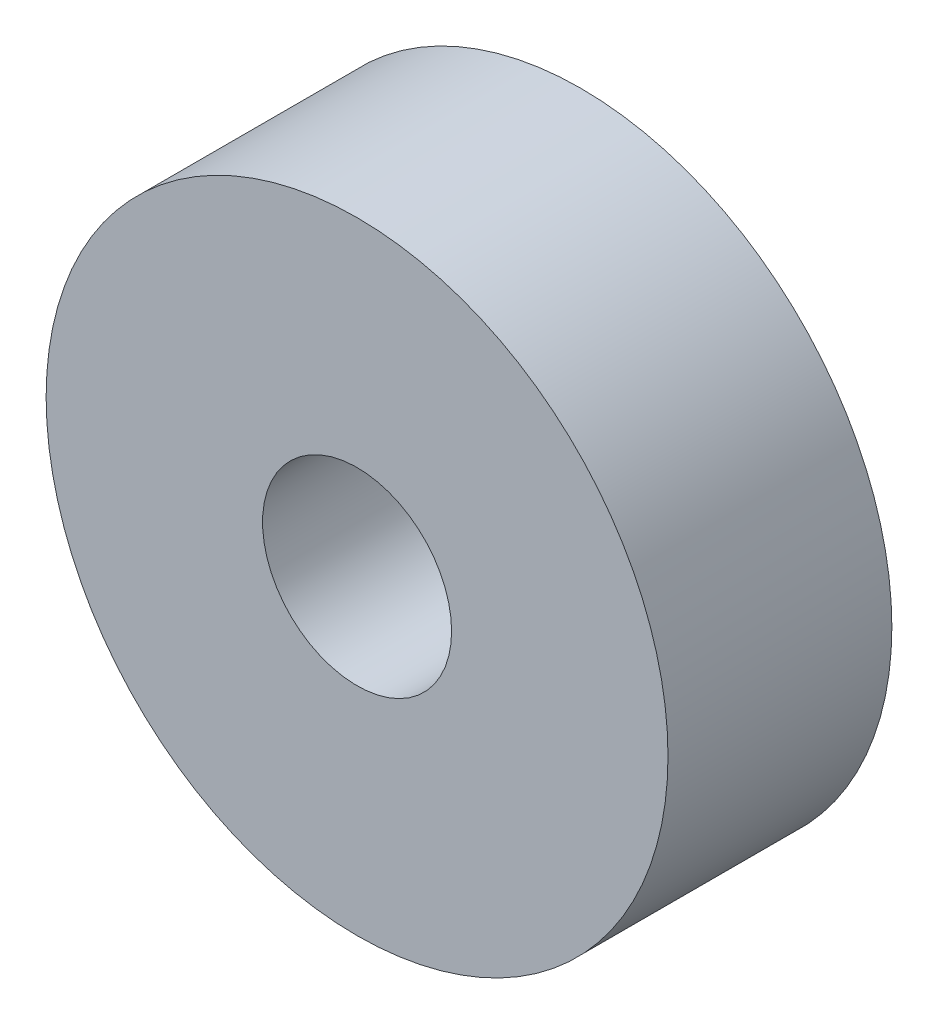
SolidWorks part; units mm, degrees
ref_plane "前视基准面" through (0, 0, 0) normal (0, 0, 1) x (1, 0, 0)
ref_plane "上视基准面" through (0, 0, 0) normal (0, 1, 0) x (1, 0, 0)
ref_plane "右视基准面" through (0, 0, 0) normal (1, 0, 0) x (0, 0, -1)
other "Configuration Table"
sketch "草图1" plane through (0, 0, 0) normal (0, 0, 1) x (1, 0, 0)
  circle A0 centre (0, 0) radius 12.5
  dimension "diameter" = 25
extrude "Sleeve" add sketch "草图1" along normal blind 9
sketch "草图2" plane through (0, 0, 9) normal (0, 0, 1) x (1, 0, 0)
  circle A0 centre (0, 0) radius 3.8
  dimension "diameter" = 7.6
extrude "Bore" cut sketch "草图2" against normal through all
